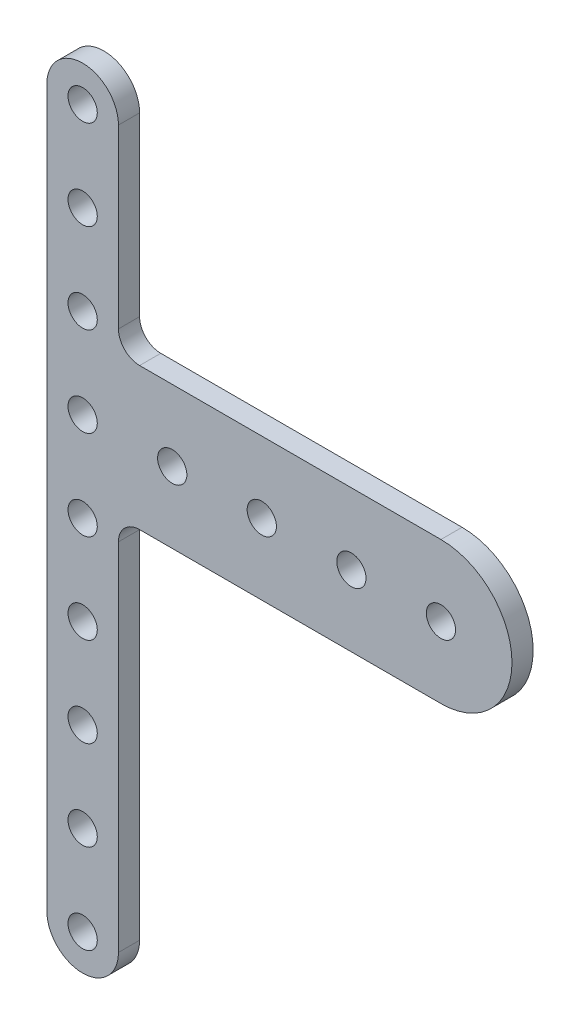
SolidWorks part; units mm, degrees
ref_plane "Front Plane" through (0, 0, 0) normal (0, 0, 1) x (1, 0, 0)
ref_plane "Top Plane" through (0, 0, 0) normal (0, 1, 0) x (1, 0, 0)
ref_plane "Right Plane" through (0, 0, 0) normal (1, 0, 0) x (0, 0, -1)
sketch "Sketch1" plane through (0, 0, 0) normal (0, 0, 1) x (1, 0, 0)
  line L0 (0, 0) -> (0, 33.025) construction
  line L1 (-5.075, 38.1) -> (-5.075, -63.5)
  line L2 (0, -63.5) -> (0, -61.425) construction
  line L3 (0, 0) -> (5.075, 0) construction
  line L4 (5.075, -63.5) -> (5.075, -10.075)
  line L5 (50.8, 10.075) -> (5.075, 10.075)
  line L6 (0, 33.025) -> (0, 36.025) construction
  line L7 (50.8, -10.075) -> (5.075, -10.075)
  line L8 (0, 36.025) -> (0, 38.1) construction
  line L9 (5.075, 0) -> (5.075, 10.075) construction
  line L10 (5.075, 10.075) -> (5.075, 38.1)
  line L11 (5.075, 0) -> (10.625, 0) construction
  line L12 (10.625, 0) -> (40.725, 0) construction
  line L13 (5.075, -10.075) -> (5.075, 0) construction
  line L14 (40.725, 0) -> (48.725, 0) construction
  line L15 (48.725, 0) -> (50.8, 0) construction
  line L16 (0, -61.425) -> (0, -58.425) construction
  line L17 (0, -58.425) -> (0, 0) construction
  circle A0 centre (0, 0) radius 2.075
  circle A1 centre (12.7, 0) radius 2.075
  circle A2 centre (25.4, 0) radius 2.075
  circle A3 centre (38.1, 0) radius 2.075
  circle A4 centre (50.8, 0) radius 2.075
  circle A5 centre (0, 12.7) radius 2.075
  circle A6 centre (0, 25.4) radius 2.075
  circle A7 centre (0, 38.1) radius 2.075
  circle A8 centre (0, -12.7) radius 2.075
  circle A9 centre (0, -25.4) radius 2.075
  circle A10 centre (0, -38.1) radius 2.075
  circle A11 centre (0, -50.8) radius 2.075
  circle A12 centre (0, -63.5) radius 2.075
  arc A13 (5.075, 38.1) -> (-5.075, 38.1) centre (0, 38.1) ccw
  arc A14 (-5.075, -63.5) -> (5.075, -63.5) centre (0, -63.5) ccw
  arc A15 (50.8, -10.075) -> (50.8, 10.075) centre (50.8, 0) ccw
  arc A16 (0, 33.025) -> (5.075, 38.1) centre (0, 38.1) ccw construction
  circle A17 centre (0, 38.1) radius 5.075 construction
  arc A18 (-5.075, 38.1) -> (0, 33.025) centre (0, 38.1) ccw construction
  arc A19 (50.8, 10.075) -> (40.725, 0) centre (50.8, 0) ccw construction
  circle A20 centre (50.8, 0) radius 10.075 construction
  arc A21 (40.725, 0) -> (50.8, -10.075) centre (50.8, 0) ccw construction
  arc A22 (0, -58.425) -> (-5.075, -63.5) centre (0, -63.5) ccw construction
  circle A23 centre (0, -63.5) radius 5.075 construction
  arc A24 (5.075, -63.5) -> (0, -58.425) centre (0, -63.5) ccw construction
  dimension "D4" = 4.15
  dimension "D7" = 4
  dimension "D1" = 38.1
  dimension "D2" = 63.5
  dimension "D3" = 50.8
  dimension "D6" = 12.7
  dimension "D8" = 12.7
  dimension "D10" = 12.7
  dimension "D11" = 3
  dimension "D12" = 8
  dimension "D5" = 5
  dimension "D9" = 6
extrude "Boss-Extrude2" add sketch "Sketch1" along normal mid plane 3
fillet "Fillet2" radius 3 2 edges at (5.075, -10.075, 0) (5.075, 10.075, 0)
